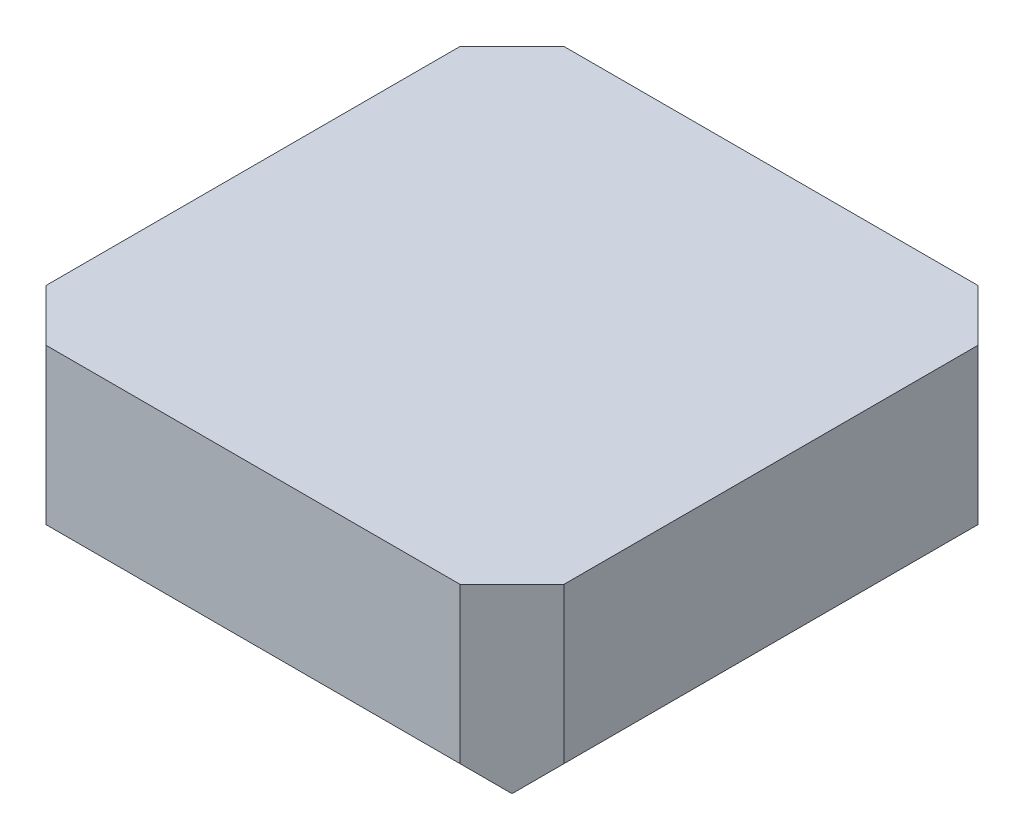
SolidWorks part; units mm, degrees
ref_plane "Plan de face" through (0, 0, 0) normal (0, 0, 1) x (1, 0, 0)
ref_plane "Plan de dessus" through (0, 0, 0) normal (0, 1, 0) x (1, 0, 0)
ref_plane "Plan de droite" through (0, 0, 0) normal (1, 0, 0) x (0, 0, -1)
sketch "Esquisse1" plane through (0, 0, 0) normal (0, 1, 0) x (1, 0, 0)
  line L1 (-5, -5) -> (5, -5)
  line L2 (-5, -5) -> (-5, 5)
  line L3 (-5, 5) -> (5, 5)
  line L4 (5, -5) -> (5, 5)
  line L5 (-5, -5) -> (5, 5) construction
  line L6 (-5, 5) -> (5, -5) construction
  point P0 (0, 0)
  dimension "D1" = 10
extrude "Boss.-Extru.1" add sketch "Esquisse1" along normal blind 6
chamfer "Chanfrein1" distance 3 angle 45 4 edges at (0, 0, -5) (-5, 0, 0) (0, 0, 5) (5, 0, 0)
chamfer "Chanfrein2" distance 1 angle 45 4 edges at (5, 4.5, -5) (5, 4.5, 5) (-5, 4.5, 5) (-5, 4.5, -5)
